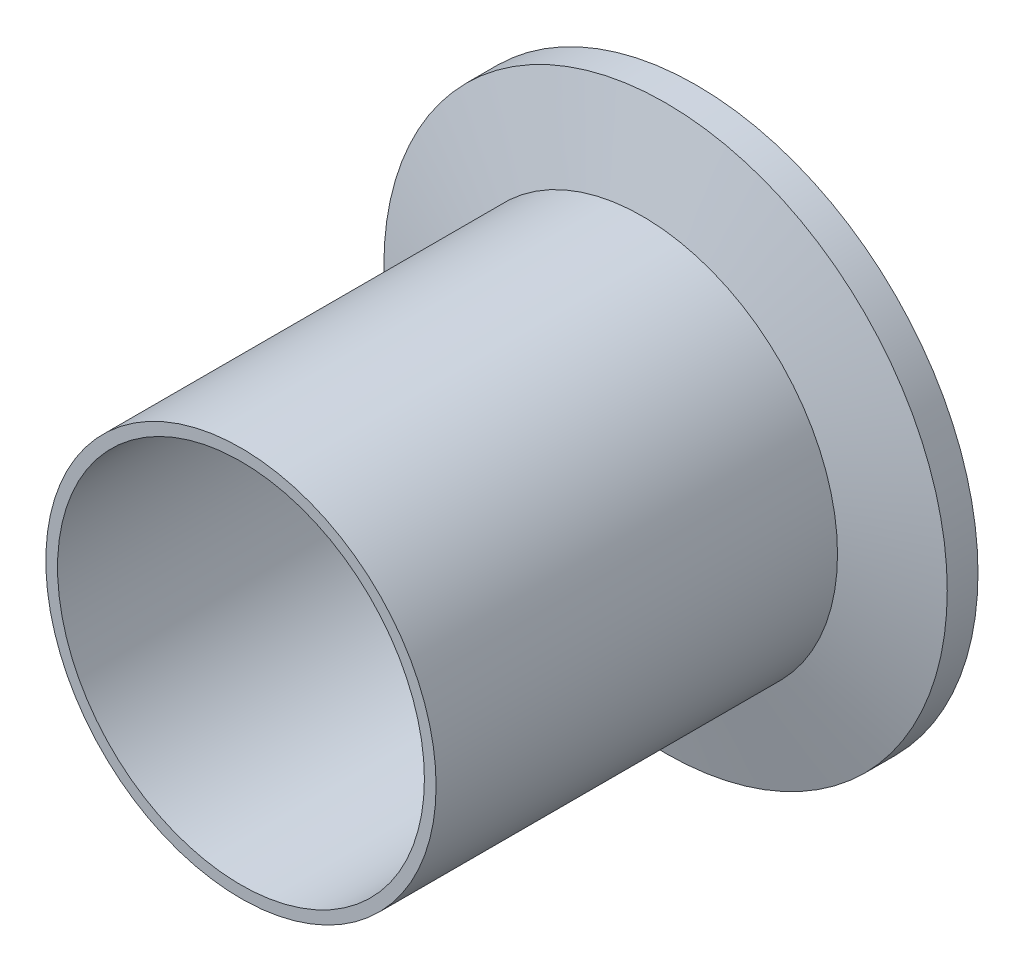
SolidWorks part; units mm, degrees
ref_plane "PL-01 Front" through (0, 0, 0) normal (0, 0, 1) x (1, 0, 0)
ref_plane "PL-02 Top" through (0, 0, 0) normal (0, 1, 0) x (1, 0, 0)
ref_plane "PL-03 Right" through (0, 0, 0) normal (1, 0, 0) x (0, 0, -1)
sketch "Sketch1" plane through (0, 0, 0) normal (1, 0, 0) x (0, 0, -1)
  line L0 (-2.8333, 0) -> (12.123, 0) construction
  line L1 (-3, 27.5) -> (0, 27.5)
  line L2 (0, 27.5) -> (0, 20.6)
  line L3 (0, 20.6) -> (-2.5, 20.6)
  line L4 (-2.5, 20.6) -> (-2.5, 17.907)
  line L5 (-2.5, 17.907) -> (-44.45, 17.907)
  line L6 (-44.45, 17.907) -> (-44.45, 19.05)
  line L7 (-44.45, 19.05) -> (-5.2642, 19.05)
  line L8 (-5.2642, 19.05) -> (-3, 27.5)
  dimension "D1" = 75
  dimension "D2" = 55
  dimension "D3" = 41.2
  dimension "D4" = 3
  dimension "D5" = 2.5
  dimension "D6" = 38.1
  dimension "D7" = 44.45
  dimension "D8" = 1.143
revolve "Revolve1" add sketch "Sketch1" angle 360 about L0
